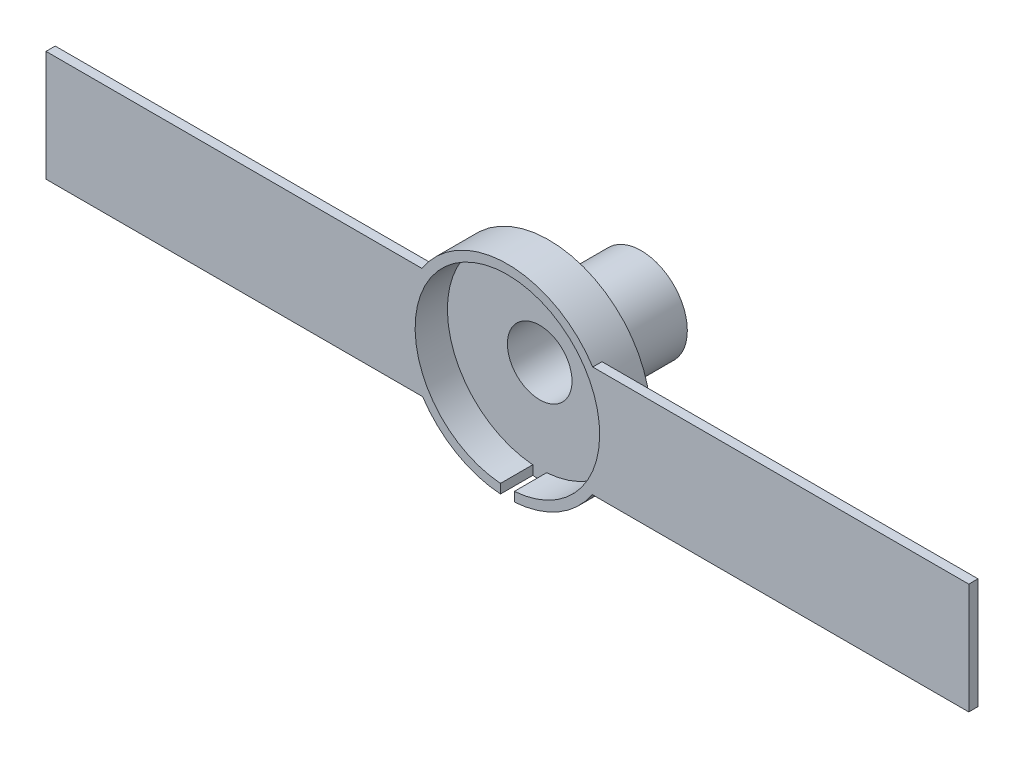
SolidWorks part; units mm, degrees
ref_plane "Front Plane" through (0, 0, 0) normal (0, 0, 1) x (1, 0, 0)
ref_plane "Top Plane" through (0, 0, 0) normal (0, 1, 0) x (1, 0, 0)
ref_plane "Right Plane" through (0, 0, 0) normal (1, 0, 0) x (0, 0, -1)
sketch "Esboço1" plane through (0, 0, 0) normal (0, 0, 1) x (1, 0, 0)
  circle A0 centre (0, 0) radius 3.5
  circle A1 centre (0, 0) radius 5
  dimension "D1" = 7
  dimension "D2" = 10
extrude "Ressalto-extrusão1" add sketch "Esboço1" along normal blind 10
sketch "Esboço2" plane through (0, 0, 10) normal (0, 0, 1) x (1, 0, 0)
  circle A0 centre (0, 0) radius 11
  circle A1 centre (0, 0) radius 3.5
  dimension "D1" = 22
extrude "Ressalto-extrusão2" add sketch "Esboço2" along normal blind 1
sketch "Esboço3" plane through (0, 0, 11) normal (0, 0, 1) x (1, 0, 0)
  circle A0 centre (0, 0) radius 10
  circle A1 centre (0, 0) radius 11
  dimension "D1" = 20
extrude "Ressalto-extrusão3" add sketch "Esboço3" along normal blind 3.5
sketch "Esboço4" plane through (0, 0, 0) normal (0, 1, 0) x (1, 0, 0)
  line L0 (0, 0) -> (0, -14.5) construction
  line L1 (-11, -14.5) -> (11, -14.5) construction
  line L3 (-0.75, -11) -> (0.75, -11)
  line L4 (-0.75, -11) -> (-0.75, -14.5)
  line L5 (-0.75, -14.5) -> (0.75, -14.5)
  line L6 (0.75, -11) -> (0.75, -14.5)
  line L7 (-0.75, -11) -> (0.75, -14.5) construction
  line L8 (-0.75, -14.5) -> (0.75, -11) construction
  point P5 (0, -12.75)
  dimension "D1" = 3.5
  dimension "D2" = 1.5
extrude "Corte-extrusão1" cut sketch "Esboço4" against normal up to surface (10.9744 mm away)
ref_plane "Plano1" through (50, 0, 0) normal (1, 0, 0) x (0, 0, -1)
sketch "Esboço8" plane through (50, 0, 0) normal (1, 0, 0) x (0, 0, -1)
  line L0 (0, 0) -> (-14, -0.0504) construction
  line L2 (-14.5, 11) -> (-14.5, -10.9744) construction
  line L3 (-14.5, -6.0504) -> (-13.5, -6.0504)
  line L4 (-14.5, -6.0504) -> (-14.5, 5.9496)
  line L5 (-14.5, 5.9496) -> (-13.5, 5.9496)
  line L6 (-13.5, -6.0504) -> (-13.5, 5.9496)
  line L7 (-14.5, -6.0504) -> (-13.5, 5.9496) construction
  line L8 (-14.5, 5.9496) -> (-13.5, -6.0504) construction
  dimension "D1" = 1
  dimension "D2" = 12
extrude "Ressalto-extrusão4" add sketch "Esboço8" against normal up to surface (40.8135 mm away)
mirror "Espelhar1" about plane through (0, 0, 0) normal (1, 0, 0) of "Ressalto-extrusão4"
